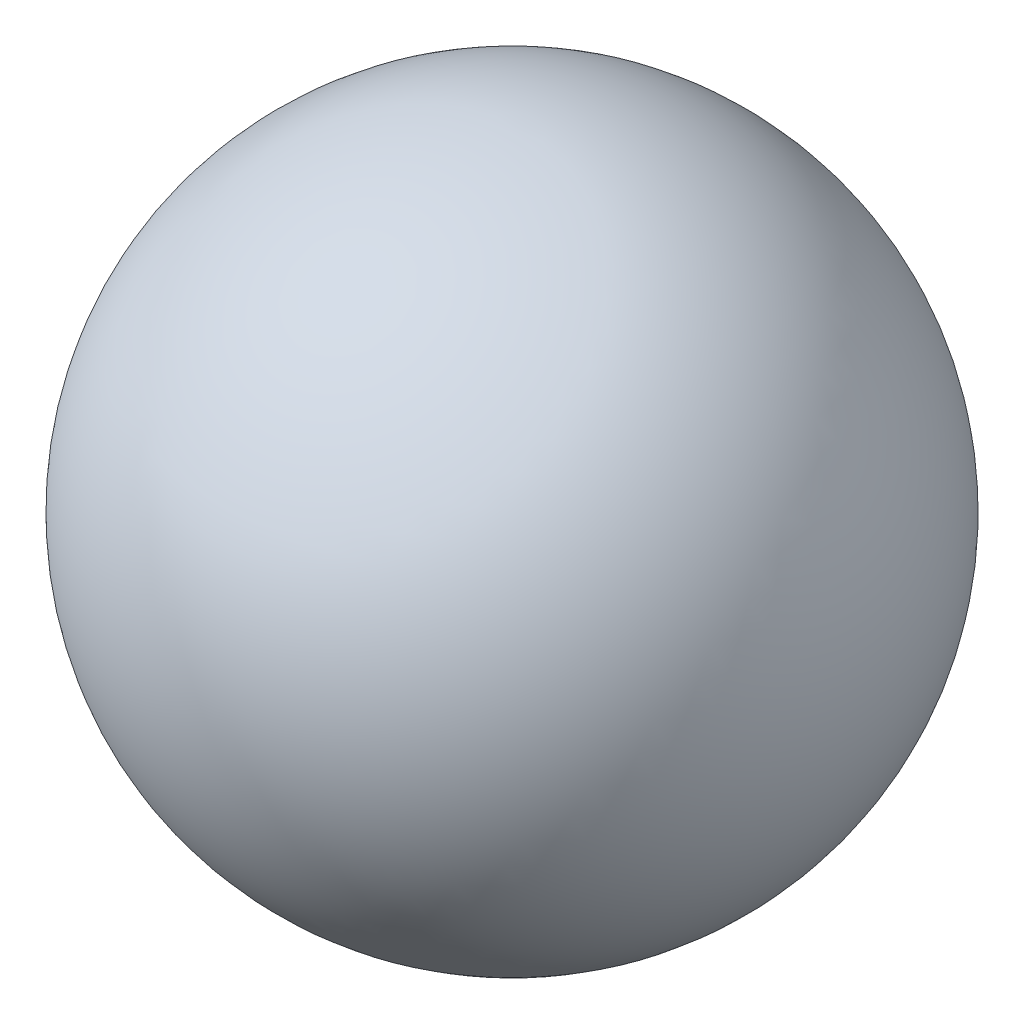
SolidWorks part; units mm, degrees
ref_plane "Front Plane" through (0, 0, 0) normal (0, 0, 1) x (1, 0, 0)
ref_plane "Top Plane" through (0, 0, 0) normal (0, 1, 0) x (1, 0, 0)
ref_plane "Right Plane" through (0, 0, 0) normal (1, 0, 0) x (0, 0, -1)
sketch "Sketch1" plane through (0, 0, 0) normal (0, 0, 1) x (1, 0, 0)
  line L0 (0, 20) -> (0, -20)
  arc A0 (0, -20) -> (0, 20) centre (0, 0) ccw
revolve "Revolve2" add sketch "Sketch1" angle 360 about L0
sketch "Sketch2" plane through (0, 0, 0) normal (0, 0, 1) x (1, 0, 0)
  line L0 (-8.7178, -18) -> (8.7178, -18)
  circle A0 centre (0, 0) radius 20 construction
  dimension "D1" = 18
extrude "Cut-Extrude1" cut sketch "Sketch2" against normal through all both and the other way through all flip side to cut
hole_wizard "M10 Tapped Hole1" positions "Sketch3" profile "Sketch4" tap size "M10" standard "DIN"
sketch "Sketch3" plane through (0, -18, 0) normal (0, -1, 0) x (-1, 0, 0)
  point P0 (0, 0)
  point P3 (0, 0)
sketch "Sketch4" plane through (0, -18, 0) normal (1, 0, 0) x (0, 0, -1)
  line L0 (0, 0) -> (0, 12.5537)
  line L1 (0, 12.5537) -> (4.25, 10)
  line L2 (4.25, 10) -> (4.25, 0)
  line L5 (4.25, 0) -> (0, 0)
  line L10 (0, 12.5537) -> (-4.25, 10) construction
  line L11 (0, -6.35) -> (0, 107.95) construction
  dimension "Tap Drill Dia." = 8.5
  dimension "Tap Drill Depth" = 10
  dimension "Drill Angle" = 118
cosmetic thread "Hole Thread1" parameters "D1"=10, "D2"=10
cosmetic thread "Hole Thread2" parameters "D1"=10, "D2"=10
